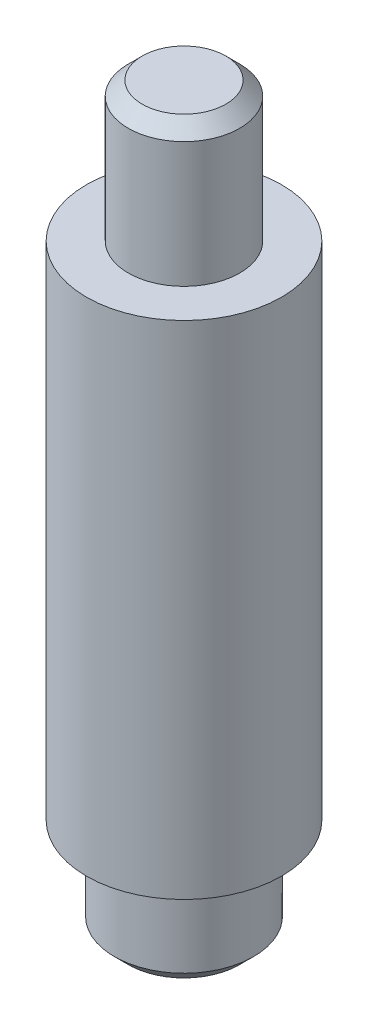
SolidWorks part; units mm, degrees
ref_plane "Plan1" through (0, 0, 0) normal (0, 0, 1) x (1, 0, 0)
ref_plane "Plan2" through (0, 0, 0) normal (0, 1, 0) x (1, 0, 0)
ref_plane "Plan3" through (0, 0, 0) normal (1, 0, 0) x (0, 0, -1)
sketch "Esquisse2" plane through (0, 0, 0) normal (1, 0, 0) x (0, 0, -1)
  line L0 (0, 0) -> (0, 44) construction
  line L1 (0, 1) -> (-4, 1)
  line L2 (-4, 1) -> (-5, 2)
  line L3 (-5, 8) -> (-5, 0) construction
  line L4 (-5, 2) -> (-5, 8)
  line L5 (-5, 8) -> (-7, 8)
  line L6 (-7, 8) -> (-7, 44)
  line L10 (-7, 44) -> (-4, 44)
  line L11 (-4, 44) -> (-4, 53)
  line L12 (-4, 53) -> (-3, 54)
  line L13 (-3, 54) -> (0, 54)
  line L14 (0, 1) -> (0, 54)
  dimension "D1" = 7
  dimension "D2" = 36
  dimension "D3" = 4
revolve "Base-Révolution" add sketch "Esquisse2" angle 360 about L0
sketch "Esquisse3" plane through (0, 0, 0) normal (1, 0, 0) x (0, 0, -1)
  line L0 (17.4929, 8) -> (17.4929, 28) construction
  line L1 (17.4929, 8) -> (17.4929, 28)
  line L2 (-17.4929, 28) -> (-17.4929, 8) construction
  line L3 (-17.4929, 28) -> (-17.4929, 8)
  dimension "D1" = 34.9857
